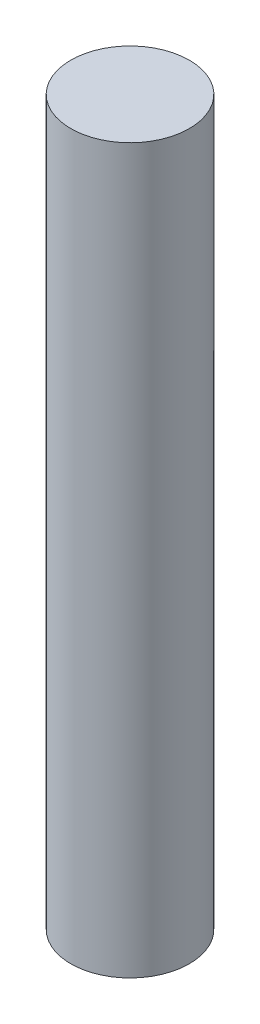
SolidWorks part; units mm, degrees
material "1023 Carbon Steel Sheet (SS)"
ref_plane "Front Plane" through (0, 0, 0) normal (0, 0, 1) x (1, 0, 0)
ref_plane "Top Plane" through (0, 0, 0) normal (0, 1, 0) x (1, 0, 0)
ref_plane "Right Plane" through (0, 0, 0) normal (1, 0, 0) x (0, 0, -1)
other "Center of Mass"
sketch "Sketch1" plane through (0, 0, 0) normal (0, 1, 0) x (1, 0, 0)
  circle A0 centre (0, 0) radius 10
  dimension "D1" = 20
extrude "Boss-Extrude1" add sketch "Sketch1" along normal mid plane 122
